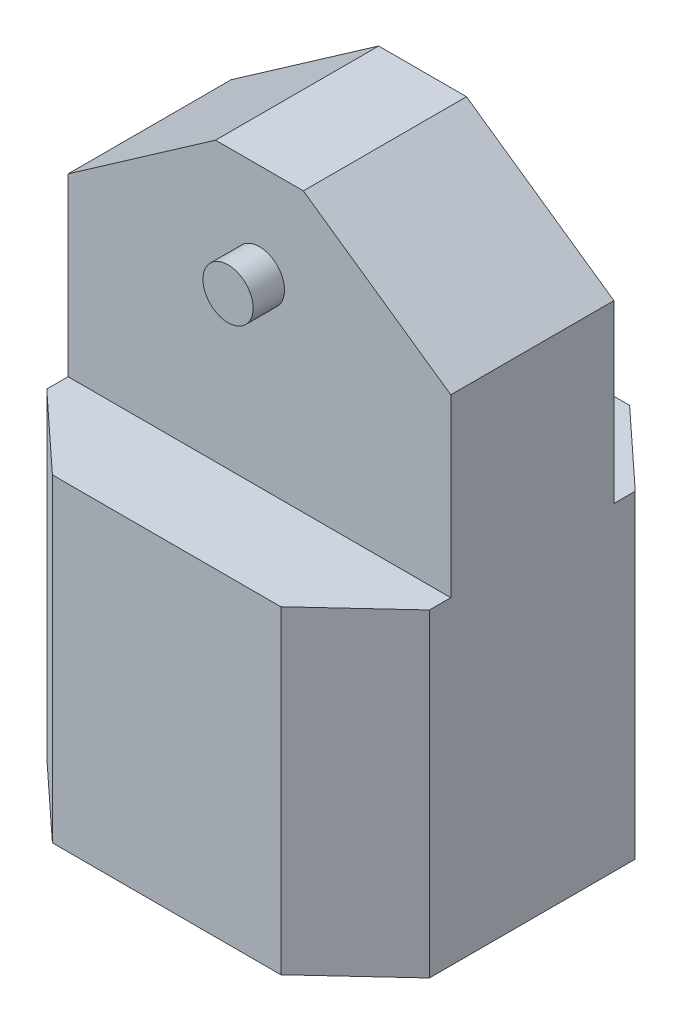
SolidWorks part; units mm, degrees
ref_plane "Спереди" through (0, 0, 0) normal (0, 0, 1) x (1, 0, 0)
ref_plane "Сверху" through (0, 0, 0) normal (0, 1, 0) x (1, 0, 0)
ref_plane "Справа" through (0, 0, 0) normal (1, 0, 0) x (0, 0, -1)
sketch "Эскиз1" plane through (0, 0, 0) normal (0, 1, 0) x (1, 0, 0)
  line L0 (-151.6931, 77.9165) -> (-151.6931, -86.0835)
  line L1 (-90.1931, 134.9165) -> (91.8069, 134.9165)
  line L2 (-151.6931, -4.0835) -> (385.0118, -4.0835) construction
  line L3 (-151.6931, 77.9165) -> (-90.1931, 134.9165)
  line L5 (-151.6931, -86.0835) -> (-90.1931, -143.0835)
  line L6 (153.3069, 77.9165) -> (91.8069, 134.9165)
  line L7 (153.3069, -86.0835) -> (91.8069, -143.0835)
  line L8 (-90.1931, -143.0835) -> (91.8069, -143.0835)
  line L9 (153.3069, 77.9165) -> (153.3069, -86.0835)
  line L10 (0.8069, -141.1933) -> (0.8069, -110.0578) construction
  dimension "D1" = 139
  dimension "D5" = 91
  dimension "D4" = 91
  dimension "D2" = 139
  dimension "D3" = 82
  dimension "D6" = 91
  dimension "D7" = 91
  dimension "D8" = 82
  dimension "D9" = 82
  dimension "D10" = 82
extrude "Вытянуть1" add sketch "Эскиз1" along normal blind 476
sketch "Sketch1" plane through (0, 0, 0) normal (0, -1, 0) x (-1, 0, 0)
  circle A0 centre (-0.8069, -4.0835) radius 21
extrude "Boss-Extrude1" add sketch "Sketch1" along normal blind 50 separate body
sketch "Sketch2" plane through (-151.6931, 0, 0) normal (-1, 0, 0) x (0, 0, 1)
  line L0 (86.0835, 0) -> (143.0835, 0) construction
  line L1 (69.0835, 520.7355) -> (248.6537, 520.7355)
  line L2 (69.0835, 520.7355) -> (69.0835, 254)
  line L3 (69.0835, 254) -> (248.6537, 254)
  line L4 (248.6537, 520.7355) -> (248.6537, 254)
  line L5 (143.0835, 476) -> (143.0835, 0) construction
  line L6 (4.0835, 476) -> (4.0835, 501.9009) construction
  line L8 (-240.4866, 520.7355) -> (-240.4866, 254)
  line L9 (-60.9165, 254) -> (-240.4866, 254)
  line L10 (-60.9165, 520.7355) -> (-60.9165, 254)
  line L11 (-60.9165, 520.7355) -> (-240.4866, 520.7355)
  dimension "D1" = 254
  dimension "D2" = 74
extrude "Cut-Extrude1" cut sketch "Sketch2" against normal through all
sketch "Sketch3" plane through (0, 0, 69.0835) normal (0, 0, 1) x (1, 0, 0)
  line L0 (-151.6931, 394) -> (-34.1931, 476)
  line L1 (-151.6931, 476) -> (-151.6931, 254) construction
  line L2 (-151.6931, 476) -> (153.3069, 476) construction
  line L3 (0.8069, 476) -> (0.8069, 337.3513) construction
  line L4 (-151.6931, 394) -> (-151.6931, 476)
  line L5 (-151.6931, 476) -> (-34.1931, 476)
  line L6 (153.3069, 476) -> (35.8069, 476)
  line L7 (153.3069, 394) -> (153.3069, 476)
  line L8 (153.3069, 394) -> (35.8069, 476)
  dimension "D1" = 394
  dimension "D2" = 70
extrude "Cut-Extrude2" cut sketch "Sketch3" against normal through all
ref_plane "Plane1" through (0, 0, 4.0835) normal (0, 0, 1) x (1, 0, 0)
sketch "Sketch4" plane through (0, 0, 4.0835) normal (0, 0, 1) x (1, 0, 0)
  circle A0 centre (0.8069, 400) radius 20
  dimension "D1" = 400
extrude "Boss-Extrude2" add sketch "Sketch4" along normal mid plane 180
